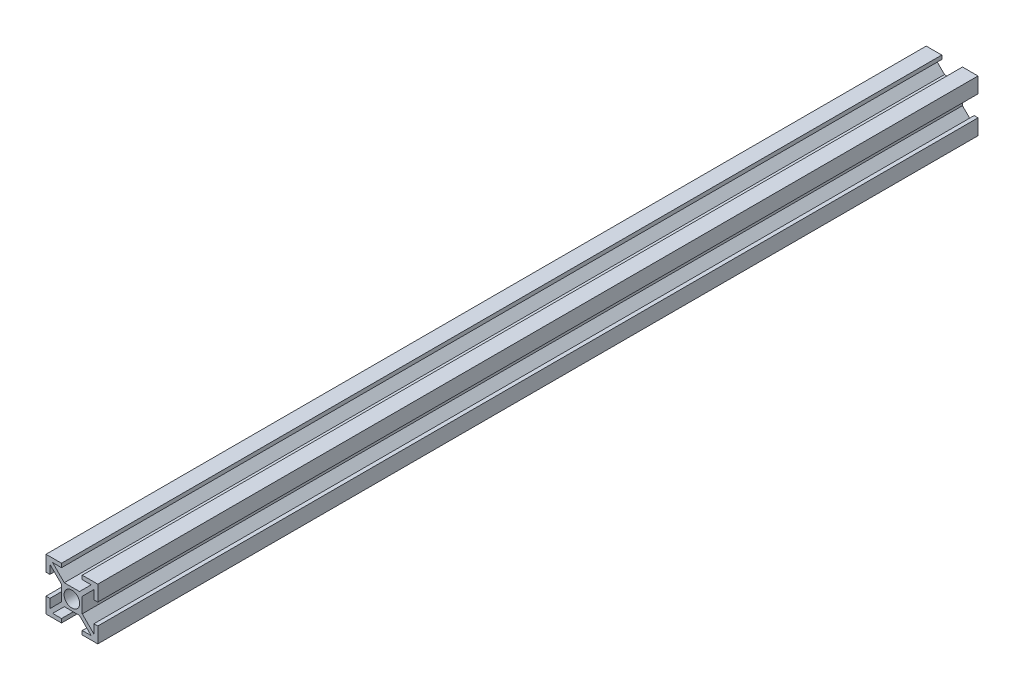
SolidWorks part; units mm, degrees
ref_plane "Plano frontal" through (0, 0, 0) normal (0, 0, 1) x (1, 0, 0)
ref_plane "Plano superior" through (0, 0, 0) normal (0, 1, 0) x (1, 0, 0)
ref_plane "Plano direito" through (0, 0, 0) normal (1, 0, 0) x (0, 0, -1)
sketch "Esboço1" plane through (0, 0, 0) normal (0, 0, 1) x (1, 0, 0)
  line L0 (-2.9393, 4) -> (2.9393, 4)
  line L1 (-10, -10) -> (-4, -10)
  line L2 (-10, -10) -> (-10, -4)
  line L3 (-10, 10) -> (-4, 10)
  line L4 (10, -10) -> (10, -4)
  line L5 (-10, -10) -> (-4, -4) construction
  line L6 (-10, 10) -> (-4, 4) construction
  line L7 (-7.4393, -8.5) -> (-2.9393, -4)
  line L8 (4, -10) -> (10, -10)
  line L9 (-8.5, -7.4393) -> (-4, -2.9393)
  line L10 (-8.5, 7.4393) -> (-4, 2.9393)
  line L11 (-7.4393, -8.5) -> (-4, -8.5)
  line L12 (-8.5, -7.4393) -> (-8.5, -4)
  line L13 (-7.4393, 8.5) -> (-4, 8.5)
  line L14 (8.5, -7.4393) -> (8.5, -4)
  line L15 (-8.5, -8.5) -> (-4, -4) construction
  line L16 (-8.5, 8.5) -> (-4, 4) construction
  line L17 (-4, 10) -> (-4, 8.5)
  line L18 (4, -8.5) -> (7.4393, -8.5)
  line L19 (-10, -4) -> (-8.5, -4)
  line L20 (4, 10) -> (4, 8.5)
  line L21 (-10, 4) -> (-8.5, 4)
  line L22 (-4, 2.9393) -> (-4, -2.9393)
  line L23 (-4, -8.5) -> (-4, -10)
  line L24 (-8.5, 4) -> (-8.5, 7.4393)
  line L25 (-10, 4) -> (-10, 10)
  line L26 (-7.4393, 8.5) -> (-2.9393, 4)
  line L27 (4, 8.5) -> (7.4393, 8.5)
  line L28 (-2.9393, -4) -> (2.9393, -4)
  line L29 (4, 10) -> (10, 10)
  line L30 (4, -8.5) -> (4, -10)
  line L31 (10, 4) -> (10, 10)
  line L32 (8.5, 4) -> (8.5, 7.4393)
  line L33 (-10.5303, -9.4697) -> (9.4697, 10.5303) construction
  line L34 (8.5, 4) -> (10, 4)
  line L35 (8.5, -4) -> (10, -4)
  line L36 (-10, -10) -> (10, 10) construction
  line L37 (4, 2.9393) -> (4, -2.9393)
  line L38 (-9.4697, -10.5303) -> (10.5303, 9.4697) construction
  line L40 (2.9393, -4) -> (7.4393, -8.5)
  line L41 (4, -4) -> (10, -10) construction
  line L42 (4, -4) -> (8.5, -8.5) construction
  line L43 (4, -2.9393) -> (8.5, -7.4393)
  line L44 (4, 0) -> (10, 0) construction
  line L45 (4, 2.9393) -> (8.5, 7.4393)
  line L46 (4, 4) -> (8.5, 8.5) construction
  line L47 (4, 4) -> (10, 10) construction
  line L48 (2.9393, 4) -> (7.4393, 8.5)
  circle A0 centre (0, 0) radius 3
  point P0 (0, 0)
  point P14 (0, 0)
  dimension "D1" = 0.75
  dimension "D3" = 1.5
  dimension "D4" = 20
  dimension "D2" = 0.75
extrude "Ressalto-extrusão1" add sketch "Esboço1" along normal blind 340
